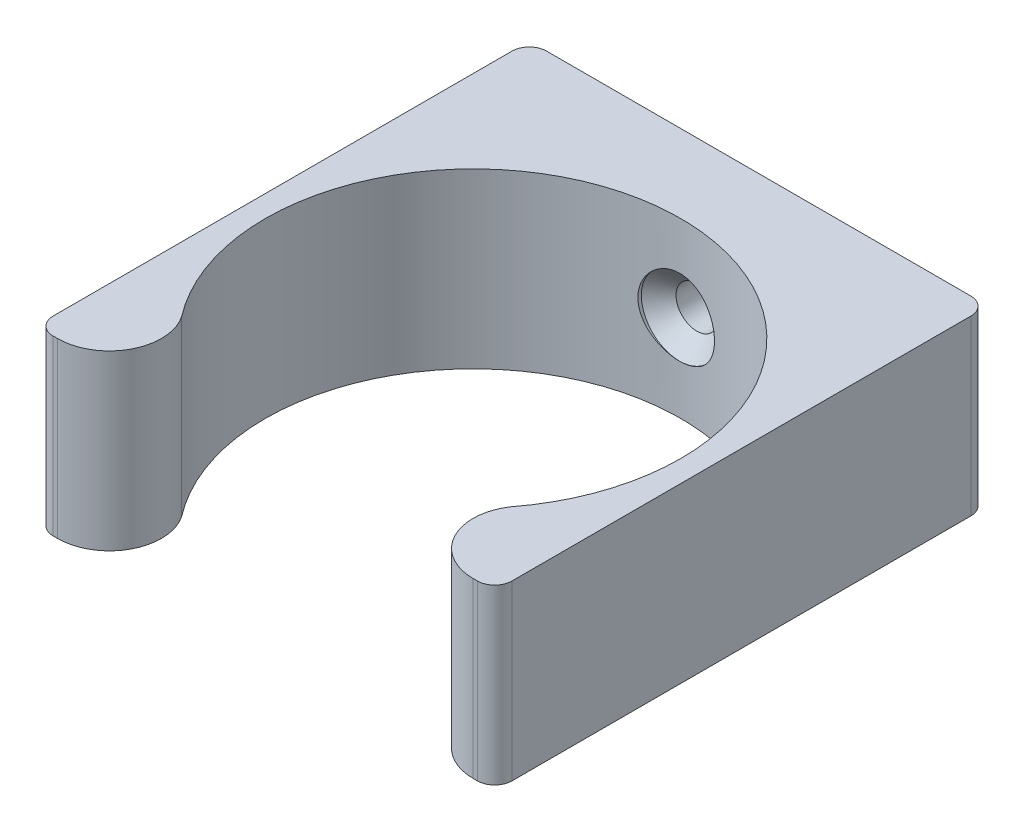
SolidWorks part; units mm, degrees
ref_plane "Front Plane" through (0, 0, 0) normal (0, 0, 1) x (1, 0, 0)
ref_plane "Top Plane" through (0, 0, 0) normal (0, 1, 0) x (1, 0, 0)
ref_plane "Right Plane" through (0, 0, 0) normal (1, 0, 0) x (0, 0, -1)
sketch "Sketch1" plane through (0, 0, 0) normal (0, 1, 0) x (1, 0, 0)
  line L7 (12.25, -12) -> (12, -12)
  line L8 (13.25, -11) -> (13.25, 15.5)
  line L9 (12.25, 16.5) -> (-12.25, 16.5)
  line L10 (-13.25, -11) -> (-13.25, 15.5)
  line L11 (-12, -12) -> (-12.25, -12)
  arc A0 (9.5076, -7.3216) -> (-9.5076, -7.3216) centre (0, 0) ccw
  arc A1 (-12, -12) -> (-9.5076, -7.3216) centre (-12, -8.9969) ccw
  arc A2 (12, -12) -> (9.5076, -7.3216) centre (12, -8.9969) cw
  arc A3 (13.25, -11) -> (12.25, -12) centre (12.25, -11) cw
  arc A4 (12.25, 16.5) -> (13.25, 15.5) centre (12.25, 15.5) cw
  arc A5 (-12.25, 16.5) -> (-13.25, 15.5) centre (-12.25, 15.5) ccw
  arc A6 (-13.25, -11) -> (-12.25, -12) centre (-12.25, -11) ccw
  point P0 (0, 0)
  point P1 (0, 0)
  point P3 (-9.5076, -7.3034)
  point P6 (9.5076, -7.3981)
  point P18 (13.25, -12)
  point P21 (13.25, 16.5)
  point P24 (-13.25, 16.5)
  dimension "D3" = 26.5
  dimension "D1" = 1
  dimension "D4" = 28.5
extrude "Boss-Extrude1" add sketch "Sketch1" along normal blind 10 contours A0 A1 L11 A6 L10 A5 L9 A4 L8 A3 L7 A2
hole_wizard "CSK for M2 Flat Head Machine Screw1" positions "3DSketch1" profile "Sketch4" countersink size "M2" standard "ANSI Metric" end condition through all
sketch3d "3DSketch1"
  point P0 (-0.0661, 5.0314, -11.9998)
sketch "Sketch4" plane through (-0.0661, 5.0314, -11.9998) normal (0, 1, 0) x (1, 0, -0.0055)
  line L0 (0, 0) -> (0, 4.5727)
  line L1 (0, 4.5727) -> (1.2, 4.5727)
  line L2 (1.2, 4.5727) -> (1.2, 1)
  line L3 (1.2, 1) -> (2.2, 0)
  line L5 (2.2, 0) -> (0, 0)
  line L6 (-1.2, 1) -> (-2.2, 0) construction
  line L11 (0, -6.35) -> (0, 107.95) construction
  dimension "Thru Hole Dia." = 2.4
  dimension "Thru Hole Depth" = 4.5727
  dimension "Near C'Sink Dia." = 4.4
  dimension "Near C'Sink Angle" = 90
